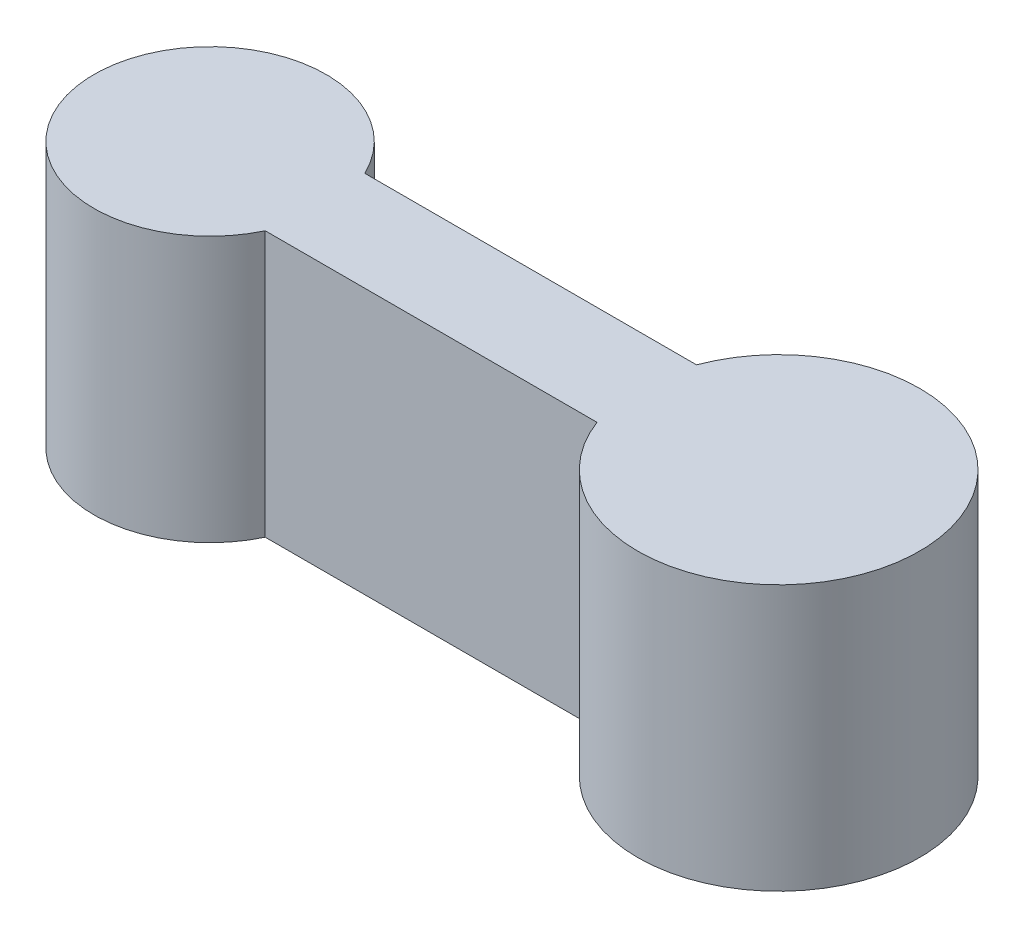
SolidWorks part; units mm, degrees
ref_plane "Front Plane" through (0, 0, 0) normal (0, 0, 1) x (1, 0, 0)
ref_plane "Top Plane" through (0, 0, 0) normal (0, 1, 0) x (1, 0, 0)
ref_plane "Right Plane" through (0, 0, 0) normal (1, 0, 0) x (0, 0, -1)
sketch "Sketch1" plane through (0, 0, 0) normal (0, 1, 0) x (1, 0, 0)
  line L0 (-13.9765, 1.5) -> (-3.9765, 1.5)
  line L1 (-13.9765, -1.5) -> (-3.9765, -1.5)
  line L2 (-17.1388, 0) -> (0, 0) construction
  arc A0 (-13.9765, 1.5) -> (-13.9765, -1.5) centre (-17.1388, 0) ccw
  arc A1 (-3.9765, -1.5) -> (-3.9765, 1.5) centre (0, 0) ccw
  dimension "D1" = 8.5
  dimension "D2" = 7
  dimension "D3" = 3
  dimension "D4" = 10
extrude "Boss-Extrude1" add sketch "Sketch1" along normal blind 8
